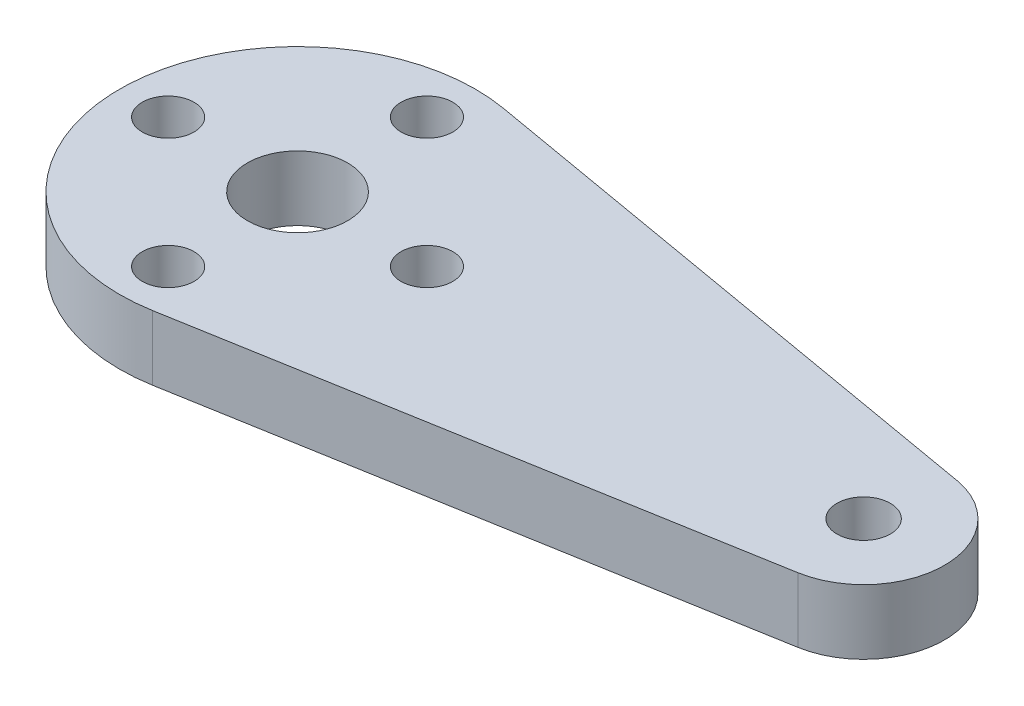
SolidWorks part; units mm, degrees
ref_plane "前视基准面" through (0, 0, 0) normal (0, 0, 1) x (1, 0, 0)
ref_plane "上视基准面" through (0, 0, 0) normal (0, 1, 0) x (1, 0, 0)
ref_plane "右视基准面" through (0, 0, 0) normal (1, 0, 0) x (0, 0, -1)
other "Configuration Table"
sketch "草图1" plane through (0, 0, 0) normal (0, 1, 0) x (1, 0, 0)
  line L0 (-15.3614, 0) -> (19.6386, 0) construction
  line L1 (-23.2216, 12.533) -> (29.9469, 3.2814)
  line L2 (-23.7121, -12.6184) -> (28.6644, -3.5046)
  circle A0 centre (-15.3614, 0) radius 11
  circle A1 centre (19.6386, 0) radius 5
  dimension "D1" = 22
  dimension "D3" = 10
  dimension "D2" = 35
extrude "凸台-拉伸1" add sketch "草图1" along normal blind 4
sketch "草图3" plane through (0, 4, 0) normal (0, 1, 0) x (1, 0, 0)
  line L0 (-15.3614, 0.0001) -> (-15.3614, 8.0001) construction
  line L1 (-15.3614, 0.0001) -> (-15.3614, -7.9999) construction
  line L2 (-15.3614, 0.0001) -> (-23.3614, 0.0001) construction
  line L3 (-15.3614, 0.0001) -> (-7.3614, 0.0001) construction
  circle A0 centre (-15.3614, 0.0001) radius 11.0001 construction
  circle A1 centre (-15.3614, 0.0001) radius 3.1
  circle A2 centre (-23.3614, 0.0001) radius 1.6
  circle A3 centre (-15.3614, 8.0001) radius 1.6
  circle A4 centre (-7.3614, 0.0001) radius 1.6
  circle A5 centre (-15.3614, -7.9999) radius 1.6
  circle A6 centre (19.6386, 0) radius 5 construction
  circle A7 centre (19.6386, 0) radius 1.65
  dimension "D1" = 6.2
  dimension "D3" = 3.2
  dimension "D4" = 3.3
  dimension "D2" = 8
extrude "切除-拉伸1" cut sketch "草图3" against normal blind 4
